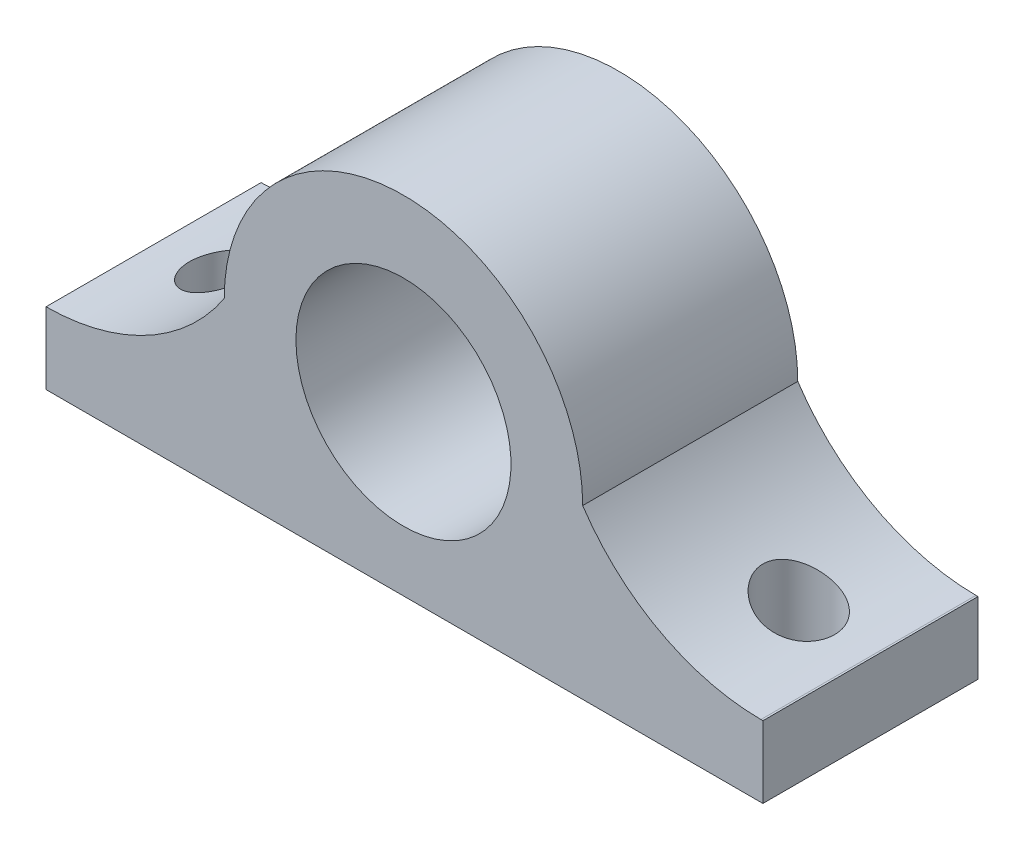
SolidWorks part; units mm, degrees
ref_plane "Front Plane" through (0, 0, 0) normal (0, 0, 1) x (1, 0, 0)
ref_plane "Top Plane" through (0, 0, 0) normal (0, 1, 0) x (1, 0, 0)
ref_plane "Right Plane" through (0, 0, 0) normal (1, 0, 0) x (0, 0, -1)
sketch "Sketch1" plane through (0, 0, 0) normal (0, 1, 0) x (1, 0, 0)
  line L1 (-5, 1.5) -> (5, 1.5)
  line L2 (-5, 1.5) -> (-5, -1.5)
  line L3 (-5, -1.5) -> (5, -1.5)
  line L4 (5, 1.5) -> (5, -1.5)
  point P0 (0, 0)
  dimension "D1" = 10
  dimension "D2" = 3
extrude "Boss-Extrude1" add sketch "Sketch1" along normal mid plane 1
sketch "Sketch3" plane through (0, 0, -1.5) normal (0, 0, -1) x (-1, 0, 0)
  line L2 (-5, 0.5) -> (-5, 0)
  line L3 (-5, 0) -> (5, 0)
  line L4 (5, 0.5) -> (5, -0.5) construction
  line L5 (5, 0) -> (5, 0.5)
  arc A0 (2.5141, 1.8417) -> (-2.4859, 1.8417) centre (0.0141, 1.8417) ccw
  arc A1 (-5, 0.5) -> (-2.4859, 1.8417) centre (-4.9859, 3.5) ccw
  arc A2 (5, 0.5) -> (2.5141, 1.8417) centre (5.0141, 3.5) cw
  dimension "D1" = 5
  dimension "D2" = 3
  dimension "D3" = 3
extrude "Boss-Extrude2" add sketch "Sketch3" against normal blind 3
sketch "Sketch4" plane through (0, 0, -1.5) normal (0, 0, -1) x (-1, 0, 0)
  circle A0 centre (0.0141, 1.8417) radius 1.5
extrude "Cut-Extrude1" cut sketch "Sketch4" against normal up to next
sketch "Sketch5" plane through (0, -0.5, 0) normal (0, -1, 0) x (1, 0, 0)
  circle A0 centre (-4, 0) radius 0.5
  circle A1 centre (4, 0) radius 0.5
extrude "Cut-Extrude2" cut sketch "Sketch5" against normal up to next
